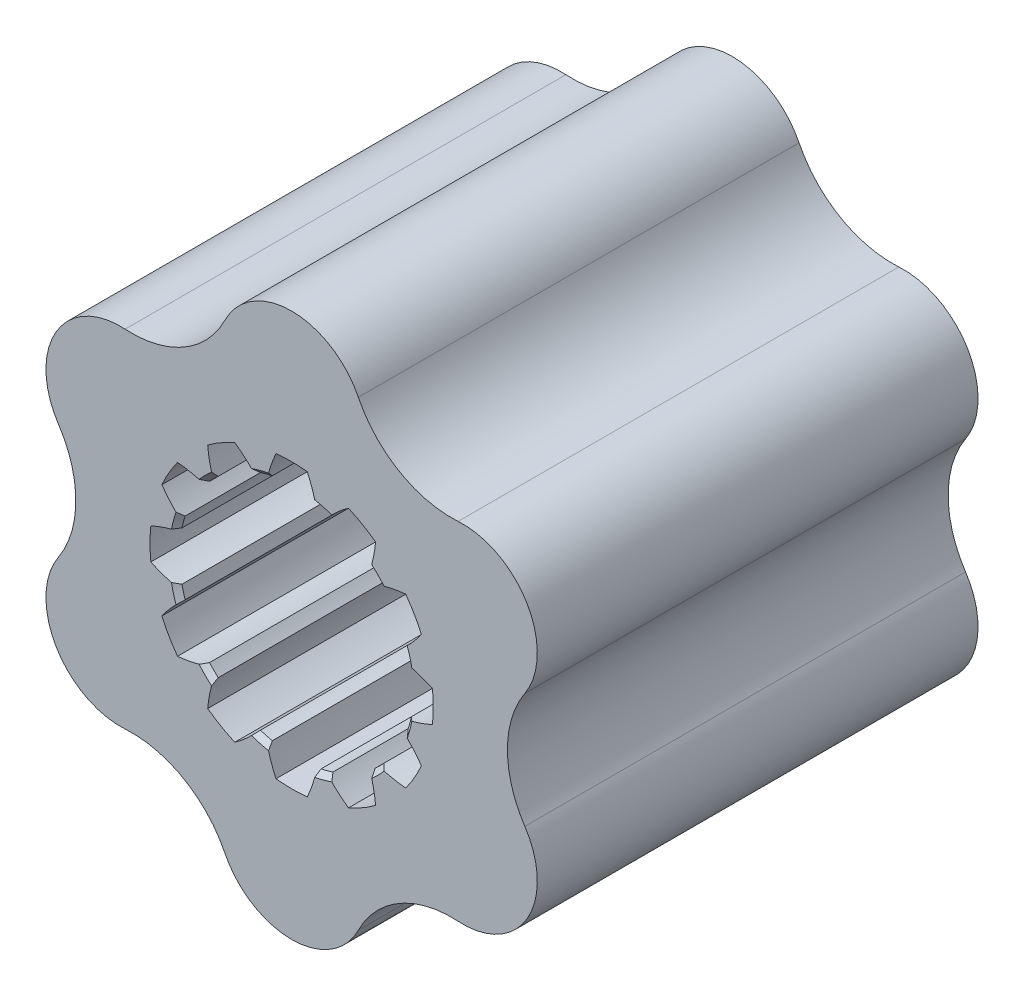
SolidWorks part; units mm, degrees
material "EN36A"
ref_plane "Front Plane" through (0, 0, 0) normal (0, 0, 1) x (1, 0, 0)
ref_plane "Top Plane" through (0, 0, 0) normal (0, 1, 0) x (1, 0, 0)
ref_plane "Right Plane" through (0, 0, 0) normal (1, 0, 0) x (0, 0, -1)
sketch "Sketch1" plane through (0, 0, 0) normal (0, 0, 1) x (1, 0, 0)
  line L0 (0, 0) -> (0, 30.3913) construction
  line L1 (0, 0) -> (36.2247, 0) construction
  line L2 (0, 0) -> (26.6587, 15.3914) construction
  line L3 (0, 0) -> (15.7458, 27.2725) construction
  circle A0 centre (0, 0) radius 26.8 construction
  circle A1 centre (0, 0) radius 21.25 construction
  circle A2 centre (0, 0) radius 11.5
  arc A3 (6.5697, 22.724) -> (-6.5697, 22.724) centre (0, 19.4675) ccw
  arc A4 (22.9644, 5.6725) -> (16.3947, 17.0515) centre (16.8593, 9.7337) ccw
  arc A5 (22.9644, -5.6725) -> (16.3947, -17.0515) centre (16.8593, -9.7337) cw
  arc A6 (6.5697, -22.724) -> (-6.5697, -22.724) centre (0, -19.4675) cw
  arc A7 (-22.9644, 5.6725) -> (-16.3947, 17.0515) centre (-16.8593, 9.7337) cw
  arc A8 (-22.9644, -5.6725) -> (-16.3947, -17.0515) centre (-16.8593, -9.7337) ccw
  arc A9 (6.5697, 22.724) -> (16.3947, 17.0515) centre (15.7458, 27.2725) ccw
  arc A10 (-6.5697, 22.724) -> (-16.3947, 17.0515) centre (-15.7458, 27.2725) cw
  arc A11 (22.9644, 5.6725) -> (22.9644, -5.6725) centre (31.4915, 0) ccw
  arc A12 (-22.9644, 5.6725) -> (-22.9644, -5.6725) centre (-31.4915, 0) cw
  arc A13 (-6.5697, -22.724) -> (-16.3947, -17.0515) centre (-15.7458, -27.2725) ccw
  arc A14 (6.5697, -22.724) -> (16.3947, -17.0515) centre (15.7458, -27.2725) cw
  dimension "D1" = 42.5
  dimension "D2" = 53.6
  dimension "D3" = 23
  dimension "D6" = 14.665
  dimension "D4" = 60
  dimension "D5" = 30
extrude "Extrude1" add sketch "Sketch1" along normal blind 43.4
sketch "Sketch4" plane through (0, 0, 0) normal (1, 0, 0) x (0, 0, -1)
  line L0 (0, 0) -> (-35.6112, 0) construction
  line L2 (0, 5.6725) -> (0, 17.0662) construction
  line L3 (0, 0) -> (-43.4, 0)
  line L4 (-0.5, 11.55) -> (-42.9, 11.55)
  line L6 (-43.4, 12.05) -> (-43.4, 0)
  line L7 (0, 12.05) -> (0, 0)
  line L8 (0, 12.05) -> (-0.5, 11.55)
  line L12 (-43.4, 17.0662) -> (-43.4, 5.6725) construction
  line L13 (-43.4, 12.05) -> (-42.9, 11.55)
  dimension "D2" = 0.5
  dimension "D3" = 45
  dimension "D4" = 23.1
  dimension "D8" = 45
revolve "Cut-Revolve1" cut sketch "Sketch4" angle 360 about L0
sketch "Sketch2" plane through (0, 0, 0) normal (0, 0, -1) x (-1, 0, 0)
  line L0 (0, 0) -> (33.1866, 0) construction
  line L1 (0, 0) -> (0, 28.3412) construction
  arc A0 (1.54, 13.8647) -> (-1.54, 13.8647) centre (0, 0) ccw
  arc A1 (-1.54, 13.8647) -> (-2.4, 11.2979) centre (9.3726, 8.7811) ccw
  arc A3 (1.54, 13.8647) -> (2.4, 11.2979) centre (-9.3726, 8.7811) cw
  arc A4 (2.4, 11.2979) -> (-2.4, 11.2979) centre (0, 0) ccw
  circle A5 centre (0, 0) radius 11.55 construction
  dimension "D1" = 27.9
  dimension "D4" = 12.0386
  dimension "D2" = 3.08
  dimension "D3" = 4.8
extrude "Extrude2" cut sketch "Sketch2" against normal up to next
pattern_circular "CirPattern1" count 12 over 360 about axis through (0, 0, 0) along (0, 0, 1) of "Extrude2"
